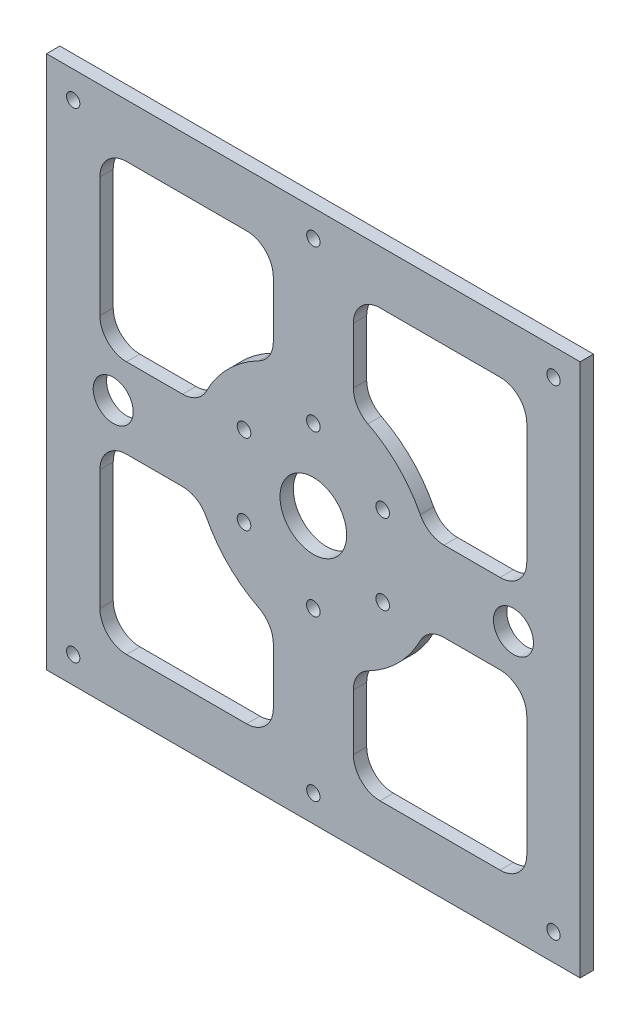
SolidWorks part; units mm, degrees
ref_plane "正面" through (0, 0, 0) normal (0, 0, 1) x (1, 0, 0)
ref_plane "平面" through (0, 0, 0) normal (0, 1, 0) x (1, 0, 0)
ref_plane "右側面" through (0, 0, 0) normal (1, 0, 0) x (0, 0, -1)
sketch "ｽｹｯﾁ1" plane through (0, 0, 0) normal (0, 0, 1) x (1, 0, 0)
  line L1 (-100, 100) -> (100, 100)
  line L2 (-100, 100) -> (-100, -100)
  line L3 (-100, -100) -> (100, -100)
  line L4 (100, 100) -> (100, -100)
  line L5 (-100, 100) -> (100, -100) construction
  line L6 (-100, -100) -> (100, 100) construction
  circle A0 centre (0, 0) radius 12.5
  point P0 (0, 0)
  dimension "D3" = 25
  dimension "D1" = 200
  dimension "D2" = 200
extrude "ﾎﾞｽ - 押し出し1" add sketch "ｽｹｯﾁ1" along normal blind 5
sketch "ｽｹｯﾁ3" plane through (0, 0, 5) normal (0, 0, 1) x (1, 0, 0)
  line L0 (100, 100) -> (-100, 100) construction
  line L1 (-90, 90) -> (90, 90) construction
  line L2 (-90, 90) -> (-90, -90) construction
  line L3 (-90, -90) -> (90, -90) construction
  line L4 (90, 90) -> (90, -90) construction
  line L5 (-90, 90) -> (90, -90) construction
  line L6 (-90, -90) -> (90, 90) construction
  line L7 (-100, 100) -> (-100, -100) construction
  circle A0 centre (0, 90) radius 2.5
  circle A1 centre (90, 90) radius 2.5
  circle A2 centre (-90, 90) radius 2.5
  circle A3 centre (-90, -90) radius 2.5
  circle A4 centre (0, -90) radius 2.5
  circle A5 centre (90, -90) radius 2.5
  point P0 (0, 0)
  dimension "D3" = 5
  dimension "D1" = 10
  dimension "D2" = 10
extrude "ｶｯﾄ - 押し出し2" cut sketch "ｽｹｯﾁ3" against normal through all
sketch "ｽｹｯﾁ4" plane through (0, 0, 5) normal (0, 0, 1) x (1, 0, 0)
  line L0 (0, 30) -> (0, 0) construction
  line L1 (-25.9808, -15) -> (0, 0) construction
  line L2 (0, 0) -> (25.9808, -15) construction
  line L3 (0, 0) -> (-75, 0) construction
  circle A0 centre (0, 30) radius 2.55
  circle A1 centre (25.9808, 15) radius 2.55
  circle A2 centre (25.9808, -15) radius 2.55
  circle A3 centre (0, -30) radius 2.55
  circle A4 centre (-25.9808, -15) radius 2.55
  circle A5 centre (-25.9808, 15) radius 2.55
  circle A6 centre (-75, 0) radius 7.5
  circle A7 centre (75, 0) radius 7.5
  dimension "D1" = 5.1
  dimension "D4" = 15
  dimension "D2" = 30
  dimension "D5" = 75
  dimension "D3" = 6
extrude "ｶｯﾄ - 押し出し3" cut sketch "ｽｹｯﾁ4" against normal through all
sketch "ｽｹｯﾁ5" plane through (0, 0, 5) normal (0, 0, 1) x (1, 0, 0)
  line L0 (-80, 70) -> (-80, 25)
  line L1 (-70, 15) -> (-48.9898, 15)
  line L4 (-15, 48.9898) -> (-15, 70)
  line L5 (-25, 80) -> (-70, 80)
  line L6 (-100, 100) -> (-100, -100) construction
  line L7 (100, 100) -> (-100, 100) construction
  line L8 (-100, 0) -> (0, 0) construction
  line L9 (0, 0) -> (0, 100) construction
  line L10 (15, 48.9898) -> (15, 70)
  line L11 (25, 80) -> (70, 80)
  line L12 (80, 70) -> (80, 25)
  line L13 (70, 15) -> (48.9898, 15)
  line L14 (15, -48.9898) -> (15, -70)
  line L15 (70, -15) -> (48.9898, -15)
  line L16 (80, -70) -> (80, -25)
  line L17 (25, -80) -> (70, -80)
  line L18 (-15, -48.9898) -> (-15, -70)
  line L19 (-25, -80) -> (-70, -80)
  line L20 (-80, -70) -> (-80, -25)
  line L21 (-70, -15) -> (-48.9898, -15)
  arc A0 (-20.4545, 40.0826) -> (-40.0826, 20.4545) centre (0, 0) ccw
  arc A1 (-80, 25) -> (-70, 15) centre (-70, 25) ccw
  arc A2 (-48.9898, 15) -> (-40.0826, 20.4545) centre (-48.9898, 25) ccw
  arc A3 (-20.4545, 40.0826) -> (-15, 48.9898) centre (-25, 48.9898) ccw
  arc A4 (-15, 70) -> (-25, 80) centre (-25, 70) ccw
  arc A5 (-80, 70) -> (-70, 80) centre (-70, 70) cw
  arc A6 (15, 70) -> (25, 80) centre (25, 70) cw
  arc A7 (80, 70) -> (70, 80) centre (70, 70) ccw
  arc A8 (80, 25) -> (70, 15) centre (70, 25) cw
  arc A9 (48.9898, 15) -> (40.0826, 20.4545) centre (48.9898, 25) cw
  arc A10 (20.4545, 40.0826) -> (15, 48.9898) centre (25, 48.9898) cw
  arc A11 (20.4545, 40.0826) -> (40.0826, 20.4545) centre (0, 0) cw
  arc A12 (20.4545, -40.0826) -> (15, -48.9898) centre (25, -48.9898) ccw
  arc A13 (20.4545, -40.0826) -> (40.0826, -20.4545) centre (0, 0) ccw
  arc A14 (48.9898, -15) -> (40.0826, -20.4545) centre (48.9898, -25) ccw
  arc A15 (80, -25) -> (70, -15) centre (70, -25) ccw
  arc A16 (80, -70) -> (70, -80) centre (70, -70) cw
  arc A17 (15, -70) -> (25, -80) centre (25, -70) ccw
  arc A18 (-15, -70) -> (-25, -80) centre (-25, -70) cw
  arc A19 (-80, -70) -> (-70, -80) centre (-70, -70) ccw
  arc A20 (-80, -25) -> (-70, -15) centre (-70, -25) cw
  arc A21 (-48.9898, -15) -> (-40.0826, -20.4545) centre (-48.9898, -25) cw
  arc A22 (-20.4545, -40.0826) -> (-15, -48.9898) centre (-25, -48.9898) cw
  arc A23 (-20.4545, -40.0826) -> (-40.0826, -20.4545) centre (0, 0) cw
  dimension "D1" = 90
  dimension "D6" = 10
  dimension "D2" = 20
  dimension "D3" = 20
  dimension "D4" = 15
  dimension "D5" = 15
extrude "ｶｯﾄ - 押し出し4" cut sketch "ｽｹｯﾁ5" against normal through all contours L0 A1 L1 A2 A0 A3 L4 A4 L5 A5
